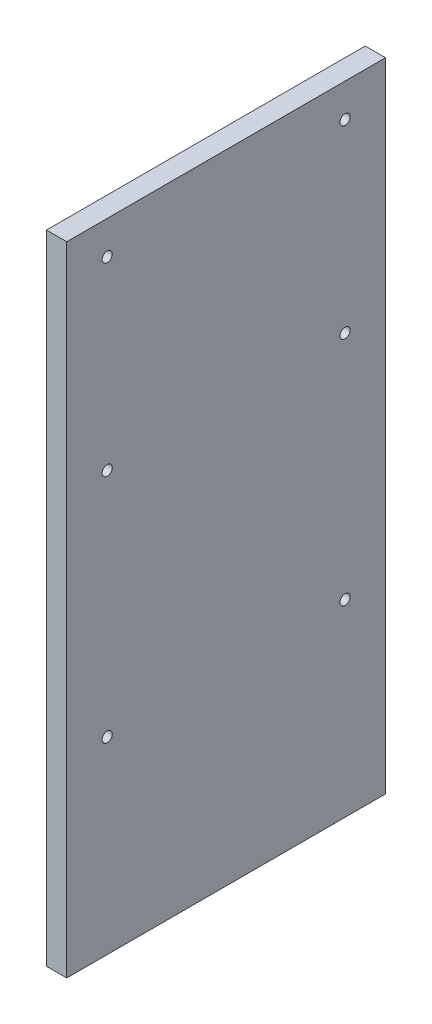
SolidWorks part; units mm, degrees
material "Maple"
ref_plane "Front Plane" through (0, 0, 0) normal (0, 0, 1) x (1, 0, 0)
ref_plane "Top Plane" through (0, 0, 0) normal (0, 1, 0) x (1, 0, 0)
ref_plane "Right Plane" through (0, 0, 0) normal (1, 0, 0) x (0, 0, -1)
sketch "Sketch1" plane through (0, 0, 0) normal (1, 0, 0) x (0, 0, -1)
  line L1 (0, 0) -> (100, 0)
  line L2 (0, 0) -> (0, -200)
  line L3 (0, -200) -> (100, -200)
  line L4 (100, 0) -> (100, -200)
  dimension "D1" = 100
  dimension "D2" = 200
extrude "Boss-Extrude1" add sketch "Sketch1" along normal blind 6.35
sketch "Sketch3" plane through (6.35, 0, 0) normal (1, 0, 0) x (0, 0, -1)
  line L0 (100, 0) -> (0, 0) construction
  line L1 (0, 0) -> (0, -200) construction
  line L2 (100, -200) -> (100, 0) construction
  circle A0 centre (12.7, -10.44) radius 1.5875
  circle A1 centre (87.3, -10.44) radius 1.5875
  circle A2 centre (12.7, -68.44) radius 1.5875
  circle A3 centre (87.3, -68.44) radius 1.5875
  circle A4 centre (12.7, -140.84) radius 1.5875
  circle A5 centre (87.3, -140.84) radius 1.5875
  point P14 (0, 0)
  point P15 (0, 0)
  dimension "D1" = 3.175
  dimension "D2" = 3.175
  dimension "D11" = 3.175
  dimension "D12" = 3.175
  dimension "D14" = 3.175
  dimension "D19" = 3.175
  dimension "D3" = 10.44
  dimension "D4" = 10.44
  dimension "D5" = 12.7
  dimension "D6" = 12.7
  dimension "D7" = 74.6
  dimension "D8" = 74.6
  dimension "D9" = 12.7
  dimension "D10" = 58
  dimension "D13" = 74.6
  dimension "D15" = 72.4
  dimension "D16" = 12.7
  dimension "D17" = 12.7
  dimension "D18" = 12.7
extrude "Cut-Extrude1" cut sketch "Sketch3" against normal blind 10
